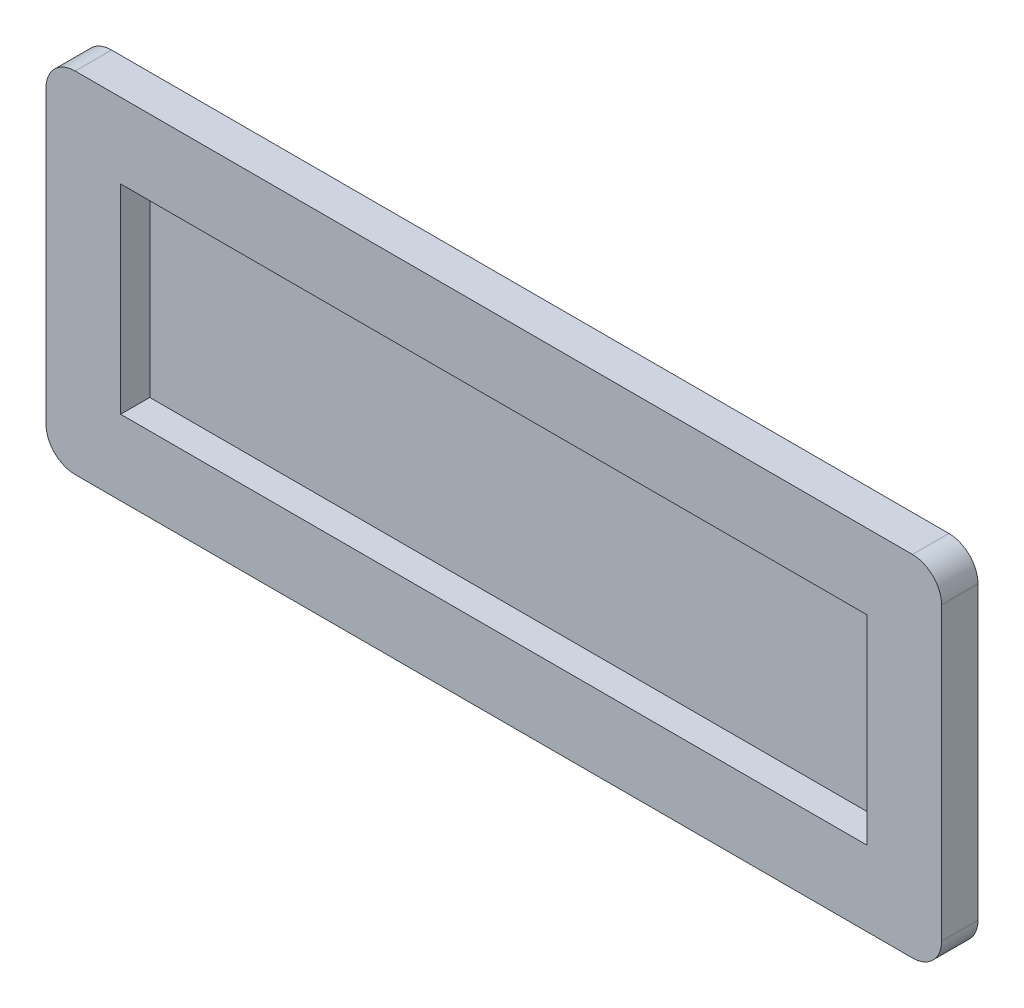
SolidWorks part; units mm, degrees
ref_plane "Plan de face" through (0, 0, 0) normal (0, 0, 1) x (1, 0, 0)
ref_plane "Plan de dessus" through (0, 0, 0) normal (0, 1, 0) x (1, 0, 0)
ref_plane "Plan de droite" through (0, 0, 0) normal (1, 0, 0) x (0, 0, -1)
sketch "Esquisse2" plane through (0, 0, 0) normal (0, 0, 1) x (1, 0, 0)
  line L1 (0, 0) -> (246, 0)
  line L2 (0, 0) -> (0, 96)
  line L3 (0, 96) -> (246, 96)
  line L4 (246, 0) -> (246, 96)
  line L5 (20.5, 75.4) -> (225.5, 75.4)
  line L6 (20.5, 75.4) -> (20.5, 20.6)
  line L7 (20.5, 20.6) -> (225.5, 20.6)
  line L8 (225.5, 75.4) -> (225.5, 20.6)
  dimension "D1" = 246
  dimension "D2" = 96
  dimension "D3" = 20.6
  dimension "D4" = 20.6
  dimension "D5" = 20.5
  dimension "D6" = 20.5
extrude "Boss.-Extru.1" add sketch "Esquisse2" along normal blind 10
fillet "Congé1" radius 8 4 edges at (246, 96, 5) (246, 0, 5) (0, 96, 5) (0, 0, 5)
sketch "Esquisse3" plane through (0, 0, 0) normal (0, 0, -1) x (-1, 0, 0)
  line L1 (-20.5, 20.6) -> (-225.5, 20.6)
  line L2 (-20.5, 20.6) -> (-20.5, 75.4)
  line L3 (-20.5, 75.4) -> (-225.5, 75.4)
  line L4 (-225.5, 20.6) -> (-225.5, 75.4)
extrude "Boss.-Extru.2" add sketch "Esquisse3" against normal blind 2
